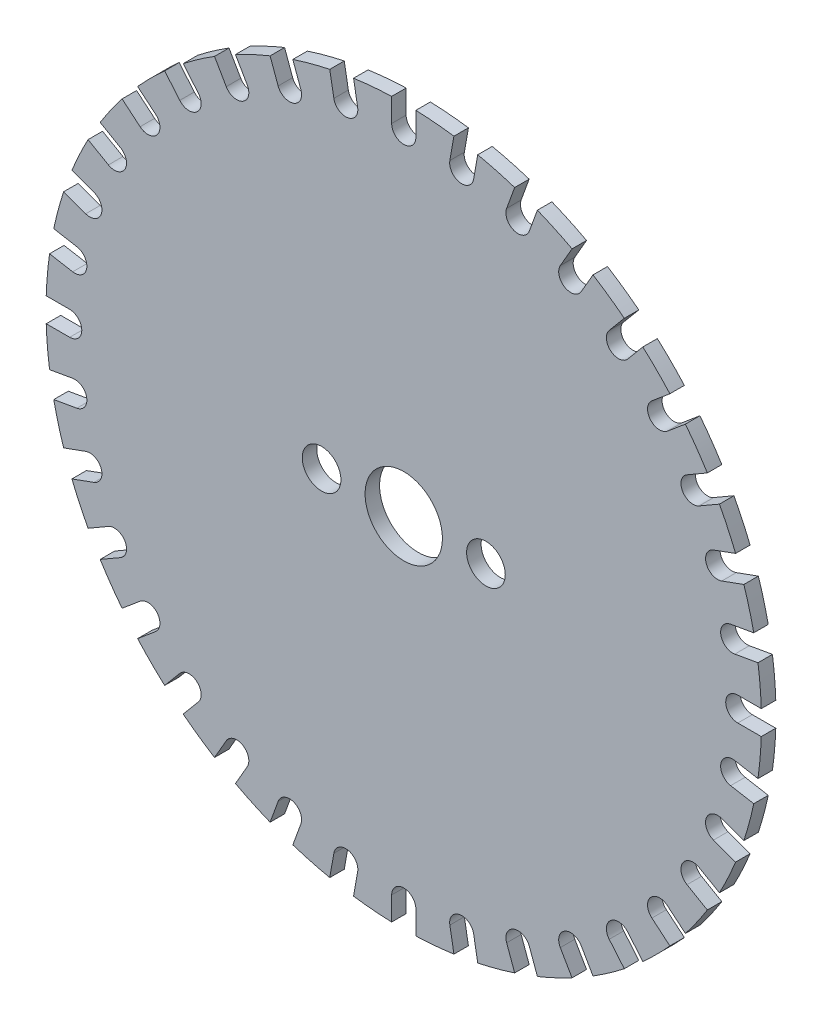
SolidWorks part; units mm, degrees
ref_plane "Plan de face" through (0, 0, 0) normal (0, 0, 1) x (1, 0, 0)
ref_plane "Plan de dessus" through (0, 0, 0) normal (0, 1, 0) x (1, 0, 0)
ref_plane "Plan de droite" through (0, 0, 0) normal (1, 0, 0) x (0, 0, -1)
sketch "Esquisse1" plane through (0, 0, 0) normal (0, 0, 1) x (1, 0, 0)
  circle A0 centre (0, 0) radius 37
  circle A1 centre (0, 0) radius 4
  circle A2 centre (8.5, 0) radius 2
  circle A3 centre (-8.5, 0) radius 2
  dimension "D1" = 74
  dimension "D2" = 8
  dimension "D4" = 4
  dimension "4" = 4
  dimension "D3" = 8.5
  dimension "D5" = 8.5
extrude "Boss.-Extru.1" add sketch "Esquisse1" along normal blind 1.5
sketch "Esquisse2" plane through (0, 0, 1.5) normal (0, 0, 1) x (1, 0, 0)
  line L0 (-40.5772, 0) -> (-34.55, 0) construction
  line L1 (-40.5772, 1.25) -> (-34.55, 1.25)
  line L2 (-40.5772, -1.25) -> (-34.55, -1.25)
  arc A0 (-40.5772, 1.25) -> (-40.5772, -1.25) centre (-40.5772, 0) ccw
  arc A1 (-34.55, -1.25) -> (-34.55, 1.25) centre (-34.55, 0) ccw
  point P3 (-37.5636, 0)
  dimension "D2" = 1.25
  dimension "D1" = 34.55
extrude "Enlèv. mat.-Extru.1" cut sketch "Esquisse2" against normal through all
pattern_circular "Répétition circulaire1" count 36 over 360 about axis through (0, 0, 0) along (0, 0, 1) of "Enlèv. mat.-Extru.1"
